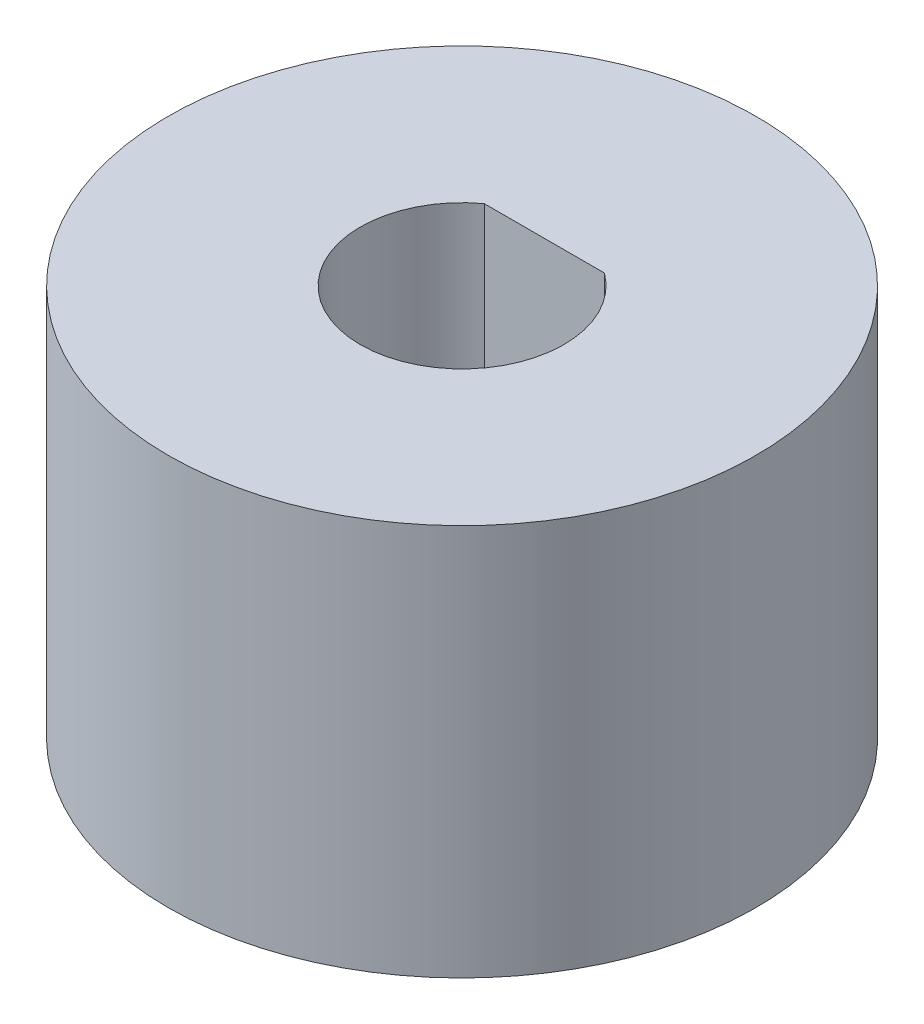
SolidWorks part; units mm, degrees
ref_plane "Front Plane" through (0, 0, 0) normal (0, 0, 1) x (1, 0, 0)
ref_plane "Top Plane" through (0, 0, 0) normal (0, 1, 0) x (1, 0, 0)
ref_plane "Right Plane" through (0, 0, 0) normal (1, 0, 0) x (0, 0, -1)
sketch "Sketch1" plane through (0, 0, 0) normal (0, 1, 0) x (1, 0, 0)
  line L0 (0, 0) -> (0, 6.2324) construction
  line L1 (-1.5, 2) -> (1.5, 2) construction
  line L2 (0, -2.5) -> (-2.5, -2.5) construction
  line L3 (-1.533, 2.1) -> (1.533, 2.1)
  circle A0 centre (0, 0) radius 7.5
  arc A2 (-1.5, 2) -> (1.5, 2) centre (0, 0) ccw construction
  arc A3 (-1.533, 2.1) -> (1.533, 2.1) centre (0, 0) ccw
  dimension "D1" = 5
  dimension "D2" = 15
  dimension "D3" = 4.5
  dimension "D4" = 0.1
extrude "Boss-Extrude1" add sketch "Sketch1" along normal blind 10
